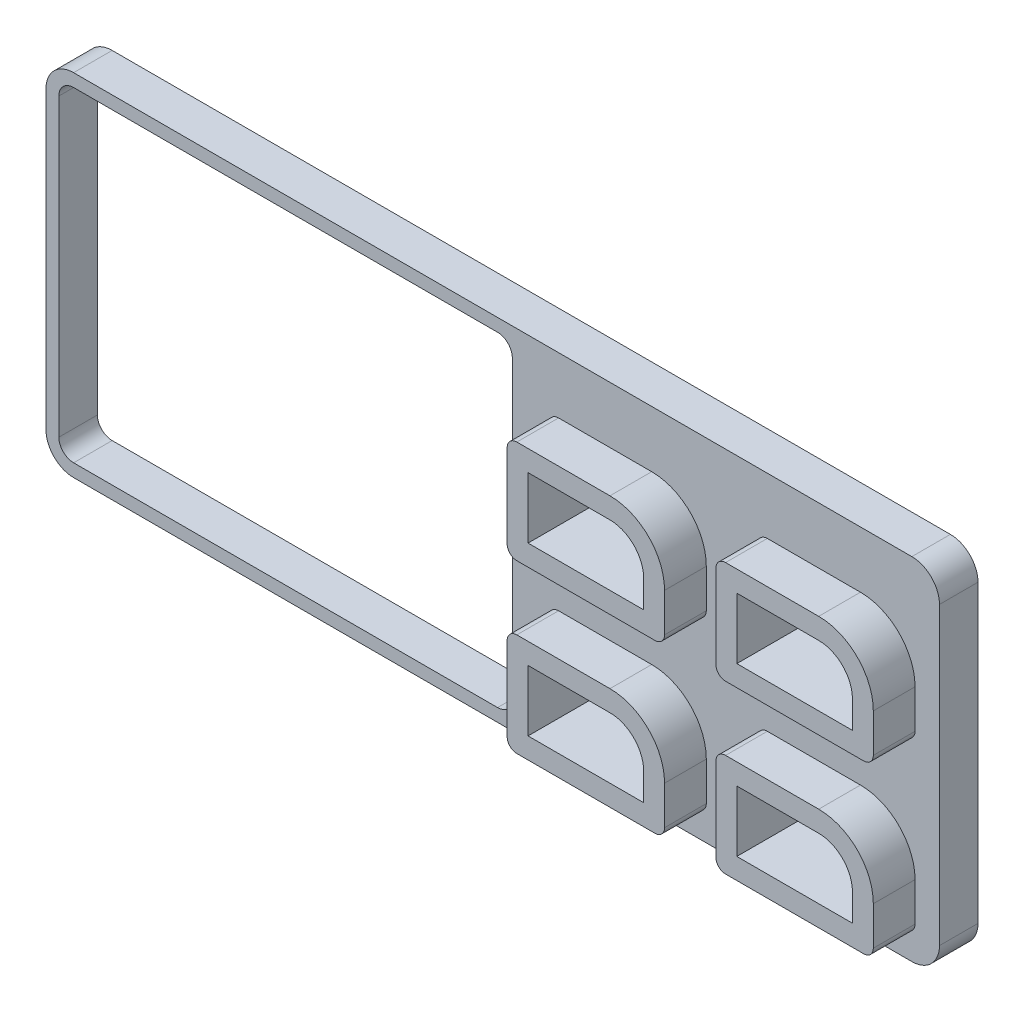
SolidWorks part; units mm, degrees
ref_plane "Plan de face" through (0, 0, 0) normal (0, 0, 1) x (1, 0, 0)
ref_plane "Plan de dessus" through (0, 0, 0) normal (0, 1, 0) x (1, 0, 0)
ref_plane "Plan de droite" through (0, 0, 0) normal (1, 0, 0) x (0, 0, -1)
sketch "Esquisse1" plane through (0, 0, 0) normal (0, 0, 1) x (1, 0, 0)
  line L1 (2, 0) -> (68, 0)
  line L2 (0, 2) -> (0, 48)
  line L3 (2, 50) -> (68, 50)
  line L4 (70, 2) -> (70, 48)
  arc A0 (68, 0) -> (70, 2) centre (68, 2) ccw
  arc A1 (0, 48) -> (2, 50) centre (2, 48) cw
  arc A2 (68, 50) -> (70, 48) centre (68, 48) cw
  arc A3 (2, 0) -> (0, 2) centre (2, 2) cw
  point P7 (70, 0)
  point P12 (70, 50)
  point P15 (0, 0)
  dimension "D3" = 2
  dimension "D1" = 70
  dimension "D2" = 50
extrude "Boss.-Extru.1" add sketch "Esquisse1" along normal blind 6
sketch "Esquisse2" plane through (0, 0, 6) normal (0, 0, 1) x (1, 0, 0)
  line L0 (35, 50) -> (35, 0) construction
  line L1 (9, 47) -> (61, 47)
  line L2 (4, 42) -> (4, 27)
  line L3 (9, 22) -> (13.5, 22)
  line L4 (66, 42) -> (66, 27)
  line L5 (68, 50) -> (2, 50) construction
  line L6 (2, 0) -> (68, 0) construction
  line L8 (7.5, 41) -> (7.5, 28)
  line L13 (10, 25.5) -> (13.5, 25.5)
  line L14 (62.5, 41) -> (62.5, 28)
  line L15 (10, 43.5) -> (60, 43.5)
  line L16 (13.5, 25.5) -> (13.5, 22)
  line L19 (56.5, 25.5) -> (56.5, 22)
  line L24 (56.5, 22) -> (61, 22)
  line L25 (56.5, 25.5) -> (60, 25.5)
  arc A0 (61, 47) -> (66, 42) centre (61, 42) cw
  arc A1 (4, 27) -> (9, 22) centre (9, 27) ccw
  arc A2 (61, 22) -> (66, 27) centre (61, 27) ccw
  arc A3 (9, 47) -> (4, 42) centre (9, 42) ccw
  arc A4 (7.5, 28) -> (10, 25.5) centre (10, 28) ccw
  arc A5 (60, 25.5) -> (62.5, 28) centre (60, 28) ccw
  arc A6 (60, 43.5) -> (62.5, 41) centre (60, 41) cw
  arc A7 (10, 43.5) -> (7.5, 41) centre (10, 41) ccw
  point P12 (66, 47)
  point P15 (4, 22)
  point P18 (66, 22)
  dimension "D4" = 5
  dimension "D6" = 3.5
  dimension "D9" = 2.5
  dimension "D1" = 62
  dimension "D2" = 25
  dimension "D3" = 3
  dimension "D5" = 3.5
  dimension "D7" = 3.5
  dimension "D8" = 3.5
  dimension "D10" = 43
extrude "Boss.-Extru.2" add sketch "Esquisse2" along normal blind 9.5
sketch "Esquisse4" plane through (0, 0, 6) normal (0, 0, 1) x (1, 0, 0)
  line L0 (2, 0) -> (68, 0) construction
  line L1 (45, 1.5) -> (66.5, 1.5)
  line L2 (43.5, 3) -> (43.5, 16)
  line L3 (45, 17.5) -> (59.5, 17.5)
  line L4 (68, 3) -> (68, 9)
  line L5 (70, 2) -> (70, 48) construction
  line L6 (46.75, 4.75) -> (46.75, 14.25)
  line L7 (46.75, 14.25) -> (59.5, 14.25)
  line L8 (64.75, 4.75) -> (64.75, 9)
  line L9 (46.75, 4.75) -> (64.75, 4.75)
  arc A0 (43.5, 16) -> (45, 17.5) centre (45, 16) cw
  arc A1 (45, 1.5) -> (43.5, 3) centre (45, 3) cw
  arc A2 (66.5, 1.5) -> (68, 3) centre (66.5, 3) ccw
  arc A3 (59.5, 17.5) -> (68, 9) centre (59.5, 9) cw
  arc A4 (46.75, 14.25) -> (46.75, 14.25) centre (46.75, 14.25) cw
  arc A5 (59.5, 14.25) -> (64.75, 9) centre (59.5, 9) cw
  arc A6 (64.75, 4.75) -> (64.75, 4.75) centre (64.75, 4.75) ccw
  arc A7 (46.75, 4.75) -> (46.75, 4.75) centre (46.75, 4.75) cw
  point P10 (43.5, 17.5)
  point P13 (43.5, 1.5)
  point P18 (68, 17.5)
  dimension "D5" = 1.5
  dimension "D6" = 8.5
  dimension "D1" = 1.5
  dimension "D2" = 2
  dimension "D3" = 24.5
  dimension "D4" = 16
  dimension "D7" = 3.25
extrude "Boss.-Extru.3" add sketch "Esquisse4" along normal blind 6.5
sketch "Esquisse5" plane through (0, 0, 6) normal (0, 0, 1) x (1, 0, 0)
  line L0 (60, 25.5) -> (56.5, 25.5) construction
  line L1 (62.5, 41) -> (62.5, 28) construction
  line L2 (10, 43.5) -> (60, 43.5) construction
  line L3 (7.5, 28) -> (7.5, 41) construction
  line L4 (46.75, 4.75) -> (64.75, 4.75)
  line L5 (64.75, 4.75) -> (64.75, 9)
  line L6 (59.5, 14.25) -> (46.75, 14.25)
  line L7 (46.75, 14.25) -> (46.75, 4.75)
  line L8 (46.75, 4.75) -> (64.75, 4.75)
  line L9 (64.75, 4.75) -> (64.75, 9)
  line L10 (59.5, 14.25) -> (46.75, 14.25)
  line L11 (46.75, 14.25) -> (46.75, 4.75)
  line L12 (60, 25.5) -> (10, 25.5)
  line L13 (62.5, 41) -> (62.5, 28)
  line L14 (10, 43.5) -> (60, 43.5)
  line L15 (7.5, 28) -> (7.5, 41)
  arc A0 (60, 25.5) -> (62.5, 28) centre (60, 28) ccw construction
  arc A1 (64.75, 9) -> (59.5, 14.25) centre (59.5, 9) ccw
  arc A2 (64.75, 9) -> (59.5, 14.25) centre (59.5, 9) ccw
  arc A3 (62.5, 41) -> (60, 43.5) centre (60, 41) ccw construction
  arc A4 (10, 43.5) -> (7.5, 41) centre (10, 41) ccw construction
  arc A5 (7.5, 28) -> (10, 25.5) centre (10, 28) ccw construction
  arc A6 (60, 25.5) -> (62.5, 28) centre (60, 28) ccw
  arc A7 (62.5, 41) -> (60, 43.5) centre (60, 41) ccw
  arc A8 (10, 43.5) -> (7.5, 41) centre (10, 41) ccw
  arc A9 (7.5, 28) -> (10, 25.5) centre (10, 28) ccw
  point P9 (10.3344, 25.5)
  dimension "D1" = 0
extrude "Enlèv. mat.-Extru.1" cut sketch "Esquisse5" against normal through all
sketch "Esquisse6" plane through (0, 0, 6) normal (0, 0, 1) x (1, 0, 0)
  line L0 (2.5, 9.5) -> (43.5, 9.5) construction
  line L2 (2, 0) -> (68, 0) construction
  line L3 (0, 48) -> (0, 2) construction
  line L4 (43.5, 16) -> (43.5, 3) construction
  text T0 "MARTIN" font "Comic Sans MS" height 7
  point P2 (5.6002, 6)
  point P6 (0, 0)
  point P9 (43.5, 6)
  dimension "D1" = 9.5
  dimension "D2" = 2.5
extrude "Enlèv. mat.-Extru.2" cut sketch "Esquisse6" against normal blind 1.25
sketch "Esquisse7" plane through (0, 0, 0) normal (0, 0, 1) x (1, 0, 0)
  line L0 (79.25, 4.75) -> (97.25, 4.75)
  line L4 (97.25, 4.75) -> (97.25, 9)
  line L5 (92, 14.25) -> (79.25, 14.25)
  line L6 (79.25, 14.25) -> (79.25, 4.75)
  line L7 (76, 16) -> (76, 3)
  line L13 (2, 52.3) -> (132.5, 52.3) construction
  line L14 (-2.3, 48) -> (-2.3, 2) construction
  line L15 (2, -2.3) -> (132.5, -2.3) construction
  line L16 (70.3, 2) -> (70.3, 48)
  line L17 (68, 50.3) -> (2, 50.3)
  line L18 (-0.3, 48) -> (-0.3, 2)
  line L19 (2, -0.3) -> (68, -0.3)
  line L20 (70.3, 2) -> (70.3, 48) construction
  line L21 (68, 50.3) -> (2, 50.3) construction
  line L22 (-0.3, 48) -> (-0.3, 2) construction
  line L23 (2, -0.3) -> (68, -0.3) construction
  line L24 (136.8, 48) -> (136.8, 2) construction
  line L25 (77.5, 1.5) -> (99, 1.5)
  line L26 (100.5, 3) -> (100.5, 9)
  line L27 (92, 17.5) -> (77.5, 17.5)
  line L28 (46.75, 4.75) -> (64.75, 4.75)
  line L29 (46.75, 14.25) -> (46.75, 4.75)
  line L30 (59.5, 14.25) -> (46.75, 14.25)
  line L31 (64.75, 4.75) -> (64.75, 9)
  line L32 (46.75, 4.75) -> (64.75, 4.75) construction
  line L33 (46.75, 14.25) -> (46.75, 4.75) construction
  line L34 (59.5, 14.25) -> (46.75, 14.25) construction
  line L35 (64.75, 4.75) -> (64.75, 9) construction
  line L36 (43.5, 16) -> (43.5, 3)
  line L37 (45, 1.5) -> (66.5, 1.5)
  line L38 (68, 3) -> (68, 9)
  line L39 (59.5, 17.5) -> (45, 17.5)
  line L40 (43.5, 16) -> (43.5, 3) construction
  line L41 (45, 1.5) -> (66.5, 1.5) construction
  line L42 (68, 3) -> (68, 9) construction
  line L43 (59.5, 17.5) -> (45, 17.5) construction
  line L44 (111.75, 4.75) -> (129.75, 4.75)
  line L45 (129.75, 4.75) -> (129.75, 9)
  line L46 (124.5, 14.25) -> (111.75, 14.25)
  line L47 (111.75, 14.25) -> (111.75, 4.75)
  line L48 (108.5, 16) -> (108.5, 3)
  line L49 (110, 1.5) -> (131.5, 1.5)
  line L50 (133, 3) -> (133, 9)
  line L51 (124.5, 17.5) -> (110, 17.5)
  line L52 (79.25, 30.75) -> (97.25, 30.75)
  line L53 (97.25, 30.75) -> (97.25, 35)
  line L54 (92, 40.25) -> (79.25, 40.25)
  line L55 (79.25, 40.25) -> (79.25, 30.75)
  line L56 (76, 42) -> (76, 29)
  line L57 (77.5, 27.5) -> (99, 27.5)
  line L58 (100.5, 29) -> (100.5, 35)
  line L59 (92, 43.5) -> (77.5, 43.5)
  line L60 (111.75, 30.75) -> (129.75, 30.75)
  line L61 (129.75, 30.75) -> (129.75, 35)
  line L62 (124.5, 40.25) -> (111.75, 40.25)
  line L63 (111.75, 40.25) -> (111.75, 30.75)
  line L64 (108.5, 42) -> (108.5, 29)
  line L65 (110, 27.5) -> (131.5, 27.5)
  line L66 (133, 29) -> (133, 35)
  line L67 (124.5, 43.5) -> (110, 43.5)
  line L68 (46.75, 30.75) -> (64.75, 30.75) [skipped]
  line L69 (64.75, 30.75) -> (64.75, 35) [skipped]
  line L70 (59.5, 40.25) -> (46.75, 40.25) [skipped]
  line L71 (46.75, 40.25) -> (46.75, 30.75) [skipped]
  line L72 (43.5, 42) -> (43.5, 29) [skipped]
  line L73 (45, 27.5) -> (66.5, 27.5) [skipped]
  line L74 (68, 29) -> (68, 35) [skipped]
  line L75 (59.5, 43.5) -> (45, 43.5) [skipped]
  arc A0 (97.25, 9) -> (92, 14.25) centre (92, 9) ccw
  arc A1 (77.5, 17.5) -> (76, 16) centre (77.5, 16) ccw
  arc A2 (76, 3) -> (77.5, 1.5) centre (77.5, 3) ccw
  arc A3 (99, 1.5) -> (100.5, 3) centre (99, 3) ccw
  arc A4 (132.5, 52.3) -> (136.8, 48) centre (132.5, 48) cw construction
  arc A5 (-2.3, 2) -> (2, -2.3) centre (2, 2) ccw construction
  arc A6 (132.5, -2.3) -> (136.8, 2) centre (132.5, 2) ccw construction
  arc A7 (2, 52.3) -> (-2.3, 48) centre (2, 48) ccw construction
  arc A12 (68, -0.3) -> (70.3, 2) centre (68, 2) ccw
  arc A13 (70.3, 48) -> (68, 50.3) centre (68, 48) ccw
  arc A14 (2, 50.3) -> (-0.3, 48) centre (2, 48) ccw
  arc A15 (-0.3, 2) -> (2, -0.3) centre (2, 2) ccw
  arc A16 (68, -0.3) -> (70.3, 2) centre (68, 2) ccw construction
  arc A17 (70.3, 48) -> (68, 50.3) centre (68, 48) ccw construction
  arc A18 (2, 50.3) -> (-0.3, 48) centre (2, 48) ccw construction
  arc A19 (-0.3, 2) -> (2, -0.3) centre (2, 2) ccw construction
  arc A20 (100.5, 9) -> (92, 17.5) centre (92, 9) ccw
  arc A21 (64.75, 9) -> (59.5, 14.25) centre (59.5, 9) ccw
  arc A22 (64.75, 9) -> (59.5, 14.25) centre (59.5, 9) ccw construction
  arc A23 (129.75, 9) -> (124.5, 14.25) centre (124.5, 9) ccw
  arc A24 (110, 17.5) -> (108.5, 16) centre (110, 16) ccw
  arc A25 (108.5, 3) -> (110, 1.5) centre (110, 3) ccw
  arc A26 (45, 17.5) -> (43.5, 16) centre (45, 16) ccw
  arc A27 (43.5, 3) -> (45, 1.5) centre (45, 3) ccw
  arc A28 (66.5, 1.5) -> (68, 3) centre (66.5, 3) ccw
  arc A29 (68, 9) -> (59.5, 17.5) centre (59.5, 9) ccw
  arc A30 (45, 17.5) -> (43.5, 16) centre (45, 16) ccw construction
  arc A31 (43.5, 3) -> (45, 1.5) centre (45, 3) ccw construction
  arc A32 (66.5, 1.5) -> (68, 3) centre (66.5, 3) ccw construction
  arc A33 (68, 9) -> (59.5, 17.5) centre (59.5, 9) ccw construction
  arc A34 (131.5, 1.5) -> (133, 3) centre (131.5, 3) ccw
  arc A35 (133, 9) -> (124.5, 17.5) centre (124.5, 9) ccw
  arc A36 (97.25, 35) -> (92, 40.25) centre (92, 35) ccw
  arc A37 (77.5, 43.5) -> (76, 42) centre (77.5, 42) ccw
  arc A38 (76, 29) -> (77.5, 27.5) centre (77.5, 29) ccw
  arc A39 (99, 27.5) -> (100.5, 29) centre (99, 29) ccw
  arc A40 (100.5, 35) -> (92, 43.5) centre (92, 35) ccw
  arc A41 (129.75, 35) -> (124.5, 40.25) centre (124.5, 35) ccw
  arc A42 (110, 43.5) -> (108.5, 42) centre (110, 42) ccw
  arc A43 (108.5, 29) -> (110, 27.5) centre (110, 29) ccw
  arc A44 (131.5, 27.5) -> (133, 29) centre (131.5, 29) ccw
  arc A45 (133, 35) -> (124.5, 43.5) centre (124.5, 35) ccw
  arc A46 (64.75, 35) -> (59.5, 40.25) centre (59.5, 35) ccw [skipped]
  arc A47 (45, 43.5) -> (43.5, 42) centre (45, 42) ccw [skipped]
  arc A48 (43.5, 29) -> (45, 27.5) centre (45, 29) ccw [skipped]
  arc A49 (66.5, 27.5) -> (68, 29) centre (66.5, 29) ccw [skipped]
  arc A50 (68, 35) -> (59.5, 43.5) centre (59.5, 35) ccw [skipped]
  point P17 (136.5291, -6.0504)
  point P28 (0, 0)
  point P40 (1.9638, 48.0362)
  dimension "D3" = 2
  dimension "D9" = 8
  dimension "D10" = 10
  dimension "D11" = 2
  dimension "D12" = 3.8
  dimension "D1" = 0.3
  dimension "D5" = 0
  dimension "D6" = 0
  dimension "D7" = 3
  dimension "D8" = 2
extrude "Boss.-Extru.4" add sketch "Esquisse7" along normal up to surface (12.5 mm away) separate body contours L26 A20 L27 A1 L7 A2 L25 A3 A0 L4 L0 L6 L5 | L58 A40 L59 A37 L56 A38 L57 A39 A36 L53 L52 L55 L54 | L66 A45 L67 A42 L64 A43 L65 A44 A41 L61 L60 L63 L62 | L50 A35 L51 A24 L48 A25 L49 A34 A23 L45 L44 L47 L46 up to face at (55.0562, 8.8062, 12.5)
sketch "Esquisse8" plane through (0, 0, 0) normal (0, 0, 1) x (1, 0, 0)
  line L0 (136.8, 48) -> (136.8, 2) construction
  line L1 (2, -2.3) -> (132.5, -2.3) construction
  line L2 (-2.3, 48) -> (-2.3, 2) construction
  line L3 (2, 52.3) -> (132.5, 52.3) construction
  line L4 (136.8, 48) -> (136.8, 2)
  line L5 (2, -2.3) -> (132.5, -2.3)
  line L6 (-2.3, 48) -> (-2.3, 2)
  line L7 (2, 52.3) -> (132.5, 52.3)
  line L8 (68, 50.3) -> (2, 50.3) construction
  line L9 (-0.3, 48) -> (-0.3, 2) construction
  line L10 (2, -0.3) -> (68, -0.3) construction
  line L11 (70.3, 2) -> (70.3, 48) construction
  line L12 (68, 50.3) -> (2, 50.3)
  line L13 (-0.3, 48) -> (-0.3, 2)
  line L14 (2, -0.3) -> (68, -0.3)
  line L15 (70.3, 2) -> (70.3, 48)
  line L16 (97.25, 9) -> (97.25, 4.75) construction
  line L17 (97.25, 4.75) -> (79.25, 4.75) construction
  line L18 (79.25, 4.75) -> (79.25, 14.25) construction
  line L19 (79.25, 14.25) -> (92, 14.25) construction
  line L20 (97.25, 9) -> (97.25, 4.75)
  line L21 (97.25, 4.75) -> (79.25, 4.75)
  line L22 (79.25, 4.75) -> (79.25, 14.25)
  line L23 (79.25, 14.25) -> (92, 14.25)
  line L24 (111.75, 14.25) -> (124.5, 14.25)
  line L25 (111.75, 4.75) -> (111.75, 14.25)
  line L26 (129.75, 4.75) -> (111.75, 4.75)
  line L27 (129.75, 9) -> (129.75, 4.75)
  line L28 (111.75, 40.25) -> (124.5, 40.25)
  line L29 (111.75, 30.75) -> (111.75, 40.25)
  line L30 (129.75, 30.75) -> (111.75, 30.75)
  line L31 (129.75, 35) -> (129.75, 30.75)
  line L32 (79.25, 40.25) -> (92, 40.25)
  line L33 (79.25, 30.75) -> (79.25, 40.25)
  line L34 (97.25, 30.75) -> (79.25, 30.75)
  line L35 (97.25, 35) -> (97.25, 30.75)
  arc A0 (136.8, 48) -> (132.5, 52.3) centre (132.5, 48) ccw construction
  arc A1 (132.5, -2.3) -> (136.8, 2) centre (132.5, 2) ccw construction
  arc A2 (-2.3, 2) -> (2, -2.3) centre (2, 2) ccw construction
  arc A3 (2, 52.3) -> (-2.3, 48) centre (2, 48) ccw construction
  arc A4 (136.8, 48) -> (132.5, 52.3) centre (132.5, 48) ccw
  arc A5 (132.5, -2.3) -> (136.8, 2) centre (132.5, 2) ccw
  arc A6 (-2.3, 2) -> (2, -2.3) centre (2, 2) ccw
  arc A7 (2, 52.3) -> (-2.3, 48) centre (2, 48) ccw
  arc A8 (70.3, 48) -> (68, 50.3) centre (68, 48) ccw construction
  arc A9 (2, 50.3) -> (-0.3, 48) centre (2, 48) ccw construction
  arc A10 (-0.3, 2) -> (2, -0.3) centre (2, 2) ccw construction
  arc A11 (68, -0.3) -> (70.3, 2) centre (68, 2) ccw construction
  arc A12 (70.3, 48) -> (68, 50.3) centre (68, 48) ccw
  arc A13 (2, 50.3) -> (-0.3, 48) centre (2, 48) ccw
  arc A14 (-0.3, 2) -> (2, -0.3) centre (2, 2) ccw
  arc A15 (68, -0.3) -> (70.3, 2) centre (68, 2) ccw
  arc A16 (97.25, 9) -> (92, 14.25) centre (92, 9) ccw construction
  arc A17 (97.25, 9) -> (92, 14.25) centre (92, 9) ccw
  arc A18 (129.75, 9) -> (124.5, 14.25) centre (124.5, 9) ccw
  arc A19 (129.75, 35) -> (124.5, 40.25) centre (124.5, 35) ccw
  arc A20 (97.25, 35) -> (92, 40.25) centre (92, 35) ccw
  dimension "D3" = 16.5
  dimension "D4" = 14.5
  dimension "D1" = 2
  dimension "D2" = 2
extrude "Boss.-Extru.5" add sketch "Esquisse8" along normal up to surface (6 mm away) up to face at (20.4973, 12.4894, 6)
delete or keep bodies "Corps-Supprimer/Garder 1" type delete bodies bodies 105
